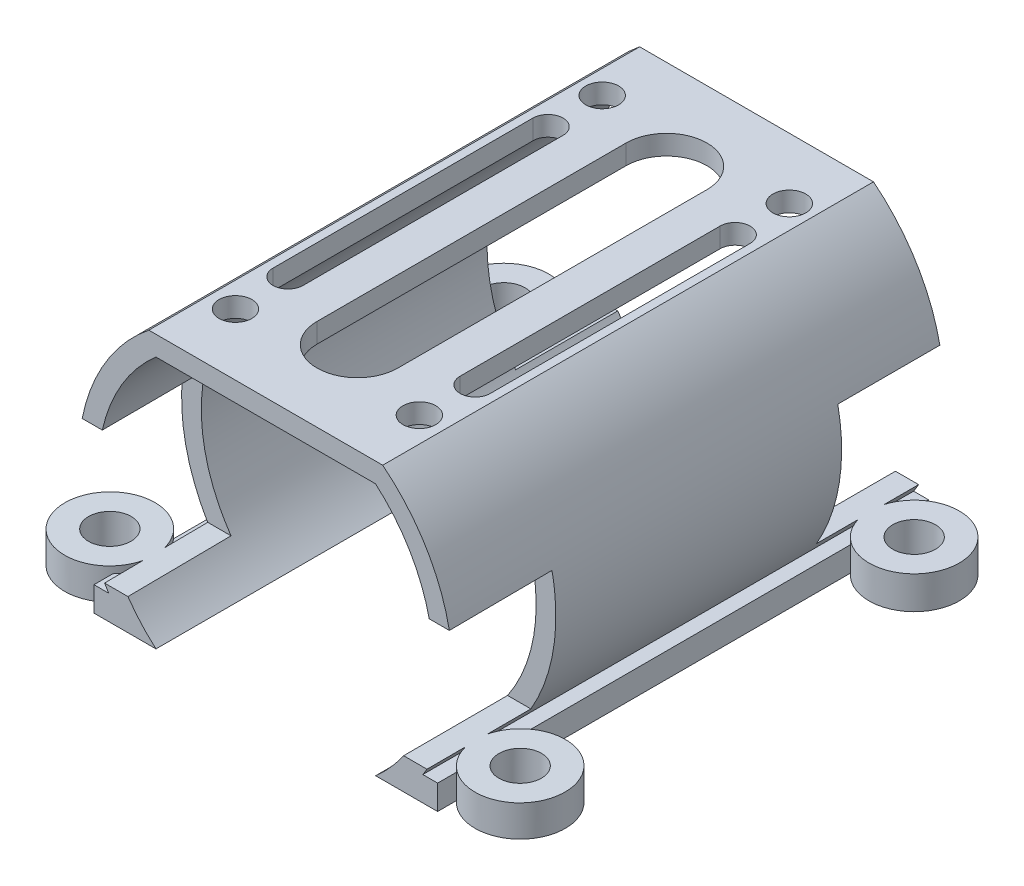
SolidWorks part; units mm, degrees
ref_plane "Alzado" through (0, 0, 0) normal (0, 0, 1) x (1, 0, 0)
ref_plane "Planta" through (0, 0, 0) normal (0, 1, 0) x (1, 0, 0)
ref_plane "Vista lateral" through (0, 0, 0) normal (1, 0, 0) x (0, 0, -1)
sketch "Croquis1" plane through (0, 0, 0) normal (0, 0, 1) x (1, 0, 0)
  line L0 (-6.6895, 7.7) -> (6.6895, 7.7)
  line L1 (-6.6895, -7.7) -> (6.6895, -7.7)
  arc A0 (-6.6895, 7.7) -> (-6.6895, -7.7) centre (0, 0) ccw
  arc A1 (6.6895, -7.7) -> (6.6895, 7.7) centre (0, 0) ccw
  dimension "D1" = 20.4
  dimension "D2" = 7.7
  dimension "D3" = 15.4
extrude "Saliente-Extruir1" add sketch "Croquis1" along normal blind 30
shell "Vaciado1" thickness 1.2
sketch "Croquis2" plane through (0, 0, -1.2) normal (0, 0, -1) x (-1, 0, 0)
  line L1 (-20.823, 15.7006) -> (20.823, 15.7006)
  line L2 (-20.823, 15.7006) -> (-20.823, -15.7006)
  line L3 (-20.823, -15.7006) -> (20.823, -15.7006)
  line L4 (20.823, 15.7006) -> (20.823, -15.7006)
  line L5 (-20.823, 15.7006) -> (20.823, -15.7006) construction
  line L6 (-20.823, -15.7006) -> (20.823, 15.7006) construction
  point P0 (0, 0)
extrude "Cortar-Extruir1" cut sketch "Croquis2" against normal blind 1.3
sketch "Croquis3" plane through (0, 0, 30) normal (0, 0, 1) x (1, 0, 0)
  line L1 (9.3098, -7.7) -> (-9.6926, -7.7)
  line L2 (9.3098, -7.7) -> (9.3098, -10.6722)
  line L3 (9.3098, -10.6722) -> (-9.6926, -10.6722)
  line L4 (-9.6926, -7.7) -> (-9.6926, -10.6722)
extrude "Cortar-Extruir2" cut sketch "Croquis3" against normal blind 48.3
sketch "Croquis4" plane through (0, -7.7, 0) normal (0, -1, 0) x (1, 0, 0)
  line L0 (0, 0) -> (0, 30) construction
  line L1 (6.6895, 30) -> (-6.6895, 30) construction
  line L2 (0, 15) -> (16.7401, 15) construction
  circle A0 centre (12.5, 3) radius 1.3
  circle A1 centre (12.5, 27) radius 1.3
  circle A2 centre (-12.5, 27) radius 1.3
  circle A3 centre (-12.5, 3) radius 1.3
  circle A4 centre (12.5, 3) radius 2.75
  circle A5 centre (12.5, 27) radius 2.75
  circle A6 centre (-12.5, 27) radius 2.75
  circle A7 centre (-12.5, 3) radius 2.75
  dimension "D3" = 2.6
  dimension "D4" = 5.5
  dimension "D1" = 12.5
  dimension "D2" = 12
extrude "Saliente-Extruir2" add sketch "Croquis4" against normal blind 2 separate body
sketch "Croquis5" plane through (0, -7.7, 0) normal (0, -1, 0) x (1, 0, 0)
  line L0 (-7.1239, 30) -> (-11.4, 30) construction
  line L1 (-8.4065, 0.1) -> (-10.4676, 0.1)
  line L2 (-8.4065, 0.1) -> (-8.4065, 30)
  line L3 (-8.4065, 30) -> (-10.4676, 30)
  line L4 (-10.4676, 0.1) -> (-10.4676, 30)
  line L5 (0, 0) -> (0, 12.3583) construction
  line L6 (10.4676, 0.1) -> (10.4676, 30)
  line L7 (8.4065, 30) -> (10.4676, 30)
  line L8 (8.4065, 0.1) -> (8.4065, 30)
  line L9 (8.4065, 0.1) -> (10.4676, 0.1)
  point P14 (8.4065, 0.1)
  point P15 (8.4065, 0.1)
extrude "Saliente-Extruir3" add sketch "Croquis5" against normal blind 1.5
sketch "Croquis6" plane through (0, 8.9, 0) normal (0, 1, 0) x (1, 0, 0)
  line L0 (0, 0) -> (0, -30) construction
  line L1 (7.1239, -30) -> (-7.1239, -30) construction
  line L2 (0, -30) -> (0, -15) construction
  line L3 (0, -15) -> (11.4, -15.05) construction
  line L4 (11.4, -30) -> (11.4, -0.1) construction
  line L5 (0, -24.4148) -> (0, -5.5852) construction
  line L6 (-2.4626, -24.4148) -> (-2.4626, -5.5852)
  line L7 (2.4626, -24.4148) -> (2.4626, -5.5852)
  line L8 (5.7, -7.1079) -> (5.7, -22.9421) construction
  line L9 (6.6165, -7.1079) -> (6.6165, -22.9421)
  line L10 (4.7835, -7.1079) -> (4.7835, -22.9421)
  line L11 (-5.7, -7.1079) -> (-5.7, -22.9421) construction
  line L12 (-6.6165, -7.1079) -> (-6.6165, -22.9421)
  line L13 (-4.7835, -7.1079) -> (-4.7835, -22.9421)
  arc A0 (-2.4626, -24.4148) -> (2.4626, -24.4148) centre (0, -24.4148) ccw
  arc A1 (2.4626, -5.5852) -> (-2.4626, -5.5852) centre (0, -5.5852) ccw
  arc A2 (6.6165, -7.1079) -> (4.7835, -7.1079) centre (5.7, -7.1079) ccw
  arc A3 (4.7835, -22.9421) -> (6.6165, -22.9421) centre (5.7, -22.9421) ccw
  circle A4 centre (5.7, -3.805) radius 1
  circle A5 centre (5.6016, -26.2446) radius 1
  arc A6 (-6.6165, -7.1079) -> (-4.7835, -7.1079) centre (-5.7, -7.1079) cw
  arc A7 (-4.7835, -22.9421) -> (-6.6165, -22.9421) centre (-5.7, -22.9421) cw
  circle A8 centre (-5.7, -3.805) radius 1
  circle A9 centre (-5.6016, -26.2446) radius 1
  point P11 (0, -15)
  point P17 (5.7, -15.025)
  point P29 (-5.7, -15.025)
  dimension "D1" = 2
extrude "Cortar-Extruir3" cut sketch "Croquis6" against normal blind 7
sketch "Croquis9" plane through (0, 0, 0) normal (1, 0, 0) x (0, 0, -1)
  line L0 (-15, -7.7) -> (-15.05, 8.9) construction
  line L1 (-25.1474, -7.7) -> (-4.8526, -7.7) construction
  line L2 (-30, 8.9) -> (-0.1, 8.9) construction
  line L3 (-27.8122, -5.7) -> (-26.1878, -5.7) construction
  line L4 (1.4687, -5.7) -> (-6.3186, -5.7)
  line L5 (1.4687, -5.7) -> (1.4687, 2.3004)
  line L6 (1.4687, 2.3004) -> (-6.3186, 2.3004)
  line L7 (-6.3186, -5.7) -> (-6.3186, 2.3004)
  line L8 (-31.5287, 2.201) -> (-23.7414, 2.2479)
  line L9 (-23.6932, -5.7523) -> (-23.7414, 2.2479)
  line L10 (-31.4805, -5.7992) -> (-23.6932, -5.7523)
  line L11 (-31.4805, -5.7992) -> (-31.5287, 2.201)
extrude "Cortar-Extruir4" cut sketch "Croquis9" against normal blind 32 and the other way blind 30
